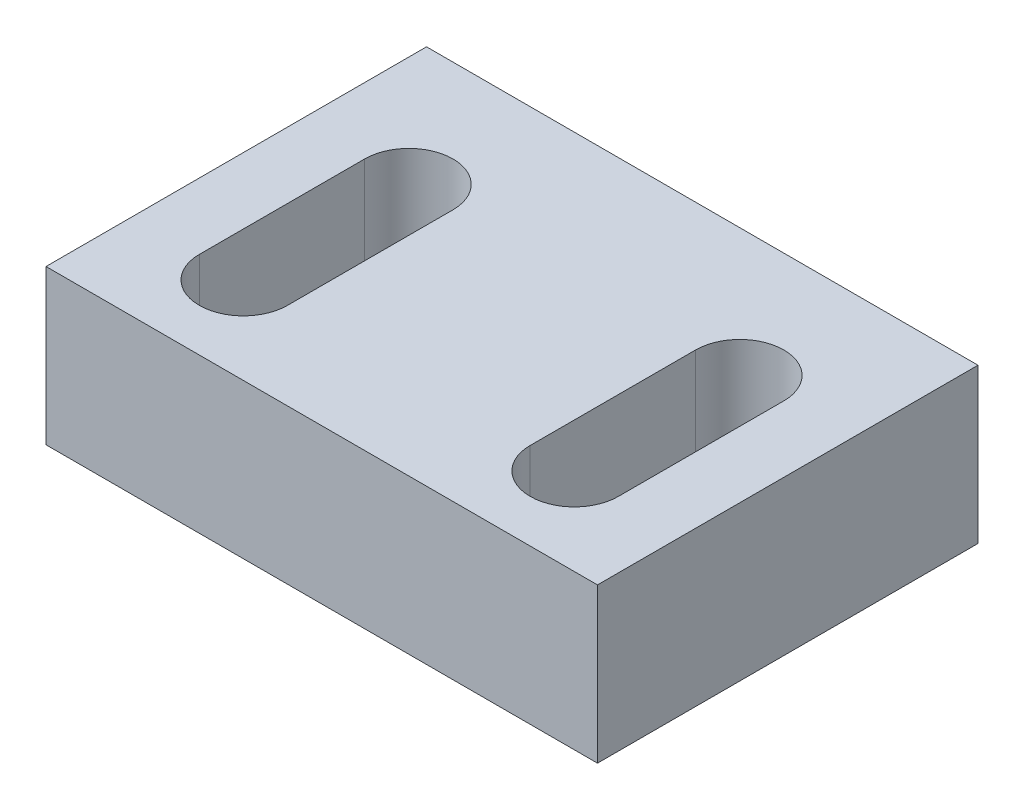
SolidWorks part; units mm, degrees
ref_plane "Front Plane" through (0, 0, 0) normal (0, 0, 1) x (1, 0, 0)
ref_plane "Top Plane" through (0, 0, 0) normal (0, 1, 0) x (1, 0, 0)
ref_plane "Right Plane" through (0, 0, 0) normal (1, 0, 0) x (0, 0, -1)
sketch "Sketch1" plane through (0, 0, 0) normal (0, 1, 0) x (1, 0, 0)
  line L0 (0, 0) -> (0, -6) construction
  line L1 (-25, 17.25) -> (25, 17.25)
  line L2 (-25, 17.25) -> (-25, -17.25)
  line L3 (-25, -17.25) -> (25, -17.25)
  line L4 (25, 17.25) -> (25, -17.25)
  line L5 (-25, 17.25) -> (25, -17.25) construction
  line L6 (-25, -17.25) -> (25, 17.25) construction
  line L7 (-15, 5.6463) -> (-15, -9.3537) construction
  line L8 (-11, 5.6463) -> (-11, -9.3537)
  line L9 (-19, 5.6463) -> (-19, -9.3537)
  line L10 (15, 5.6463) -> (15, -9.3537) construction
  line L11 (11, 5.6463) -> (11, -9.3537)
  line L12 (19, 5.6463) -> (19, -9.3537)
  arc A0 (-11, 5.6463) -> (-19, 5.6463) centre (-15, 5.6463) ccw
  arc A1 (-19, -9.3537) -> (-11, -9.3537) centre (-15, -9.3537) ccw
  arc A2 (11, 5.6463) -> (19, 5.6463) centre (15, 5.6463) cw
  arc A3 (19, -9.3537) -> (11, -9.3537) centre (15, -9.3537) cw
  point P0 (0, 0)
  point P10 (-15, -1.8537)
  point P18 (15, -1.8537)
  dimension "D3" = 4
  dimension "D1" = 34.5
  dimension "D2" = 50
  dimension "D4" = 11.25
  dimension "D5" = 15
extrude "Boss-Extrude1" add sketch "Sketch1" along normal mid plane 14
